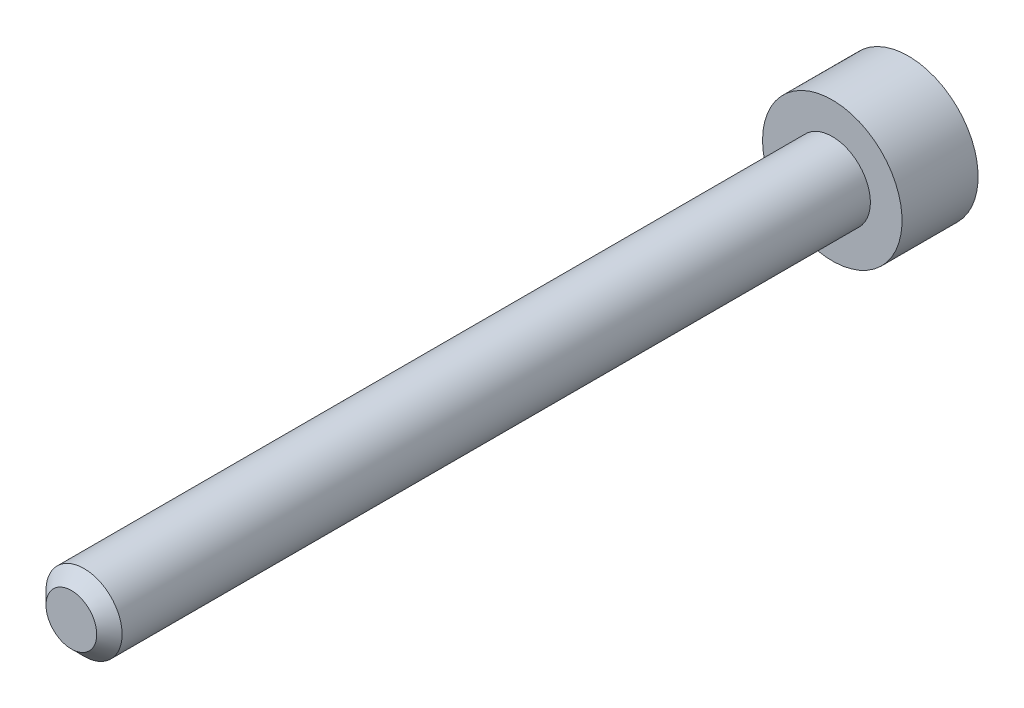
SolidWorks part; units mm, degrees
material "Alliage 1060"
ref_plane "Plan de face" through (0, 0, 0) normal (0, 0, 1) x (1, 0, 0)
ref_plane "Plan de dessus" through (0, 0, 0) normal (0, 1, 0) x (1, 0, 0)
ref_plane "Plan de droite" through (0, 0, 0) normal (1, 0, 0) x (0, 0, -1)
sketch "Esquisse2" plane through (0, 0, 0) normal (0, 0, 1) x (1, 0, 0)
  circle A0 centre (0, 0) radius 1.5
  dimension "D1" = 3
extrude "Extrusion1" add sketch "Esquisse2" along normal blind 30
sketch "Esquisse3" plane through (0, 0, 0) normal (0, 0, -1) x (-1, 0, 0)
  circle A0 centre (0, 0) radius 2.75
  dimension "D1" = 5.5
extrude "Extrusion2" add sketch "Esquisse3" along normal blind 3
chamfer "Chanfrein1" distance 0.5 angle 45 1 edges at (1.5, 0, 30)
